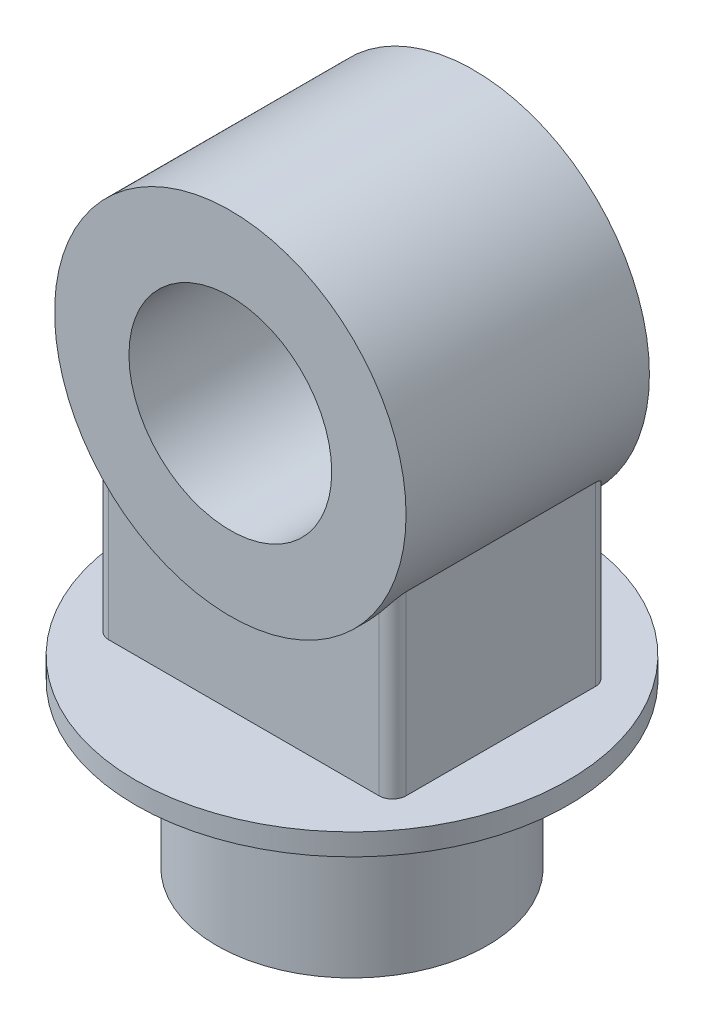
SolidWorks part; units mm, degrees
material "Aleación 6061"
ref_plane "Ön Düzlem" through (0, 0, 0) normal (0, 0, 1) x (1, 0, 0)
ref_plane "Üst Düzlem" through (0, 0, 0) normal (0, 1, 0) x (1, 0, 0)
ref_plane "Sağ Düzlem" through (0, 0, 0) normal (1, 0, 0) x (0, 0, -1)
sketch "Çizim1" plane through (0, 0, 0) normal (0, 1, 0) x (1, 0, 0)
  circle A0 centre (0, 0) radius 100
  dimension "D1" = 200
extrude "Yükseklik-Ekstrüzyon1" add sketch "Çizim1" along normal blind 120
sketch "Çizim2" plane through (0, 120, 0) normal (0, 1, 0) x (1, 0, 0)
  circle A0 centre (0, 0) radius 160
  dimension "D1" = 320
extrude "Yükseklik-Ekstrüzyon2" add sketch "Çizim2" along normal blind 16
sketch "Çizim3" plane through (0, 0, 0) normal (0, 0, 1) x (1, 0, 0)
  line L0 (0, -13.6636) -> (0, 166.1012) construction
  line L1 (160, 136) -> (-160, 136) construction
  circle A0 centre (0, 336) radius 75
  circle A1 centre (0, 336) radius 130
  dimension "D1" = 150
  dimension "D2" = 260
  dimension "D3" = 200
extrude "Yükseklik-Ekstrüzyon3" add sketch "Çizim3" against normal mid plane 180 separate body
sketch "Çizim4" plane through (0, 136, 0) normal (0, 1, 0) x (1, 0, 0)
  line L1 (-110, 80) -> (110, 80)
  line L2 (-110, 80) -> (-110, -80)
  line L3 (-110, -80) -> (110, -80)
  line L4 (110, 80) -> (110, -80)
  line L5 (-110, 80) -> (110, -80) construction
  line L6 (-110, -80) -> (110, 80) construction
  point P0 (0, 0)
  dimension "D1" = 160
  dimension "D2" = 220
extrude "Yükseklik-Ekstrüzyon4" add sketch "Çizim4" along normal up to next
fillet "Radyus1" radius 10 4 edges at (-110, 201.359, -80) (-110, 201.359, 80) (110, 201.359, -80) (110, 201.359, 80)
